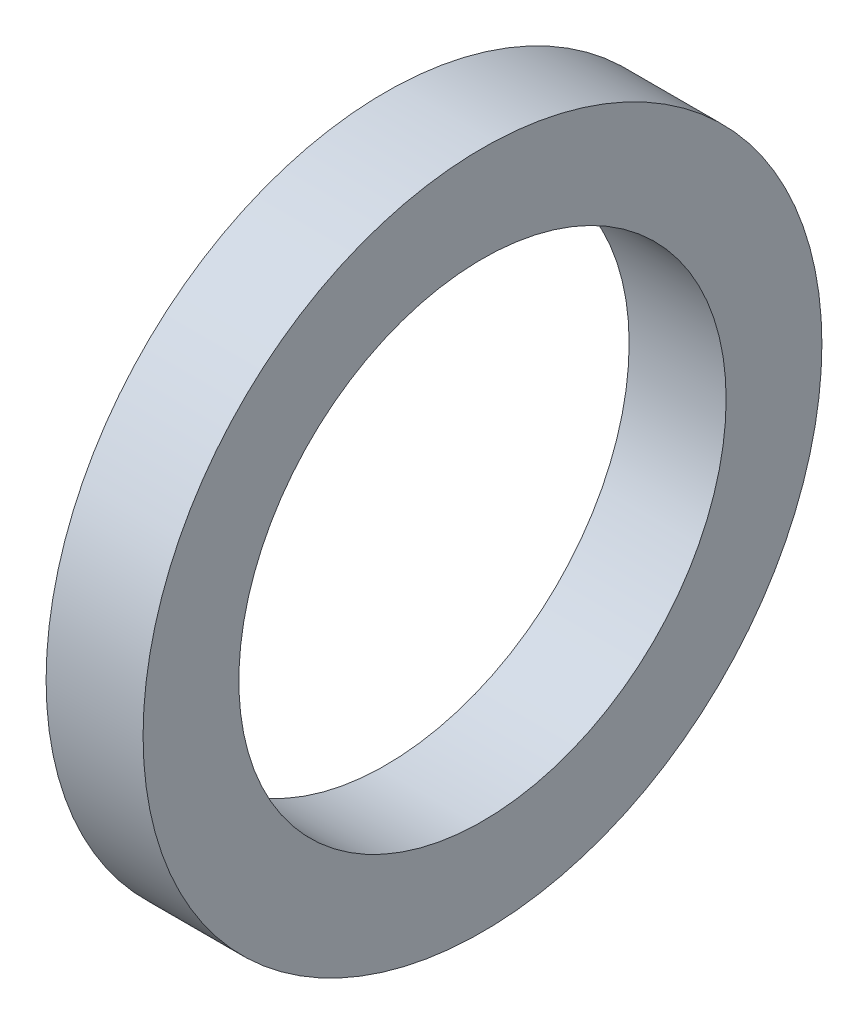
SolidWorks part; units mm, degrees
material "SS400"
ref_plane "Front Plane" through (0, 0, 0) normal (0, 0, 1) x (1, 0, 0)
ref_plane "Top Plane" through (0, 0, 0) normal (0, 1, 0) x (1, 0, 0)
ref_plane "Right Plane" through (0, 0, 0) normal (1, 0, 0) x (0, 0, -1)
sketch "Sketch1" plane through (0, 0, 0) normal (1, 0, 0) x (0, 0, -1)
  circle A0 centre (0, 0) radius 10.05
  circle A1 centre (0, 0) radius 14
  dimension "D1" = 20.1
  dimension "D2" = 28
extrude "Boss-Extrude1" add sketch "Sketch1" along normal blind 4
equation "\"Mass Kg\"= \"SW-Mass\""
